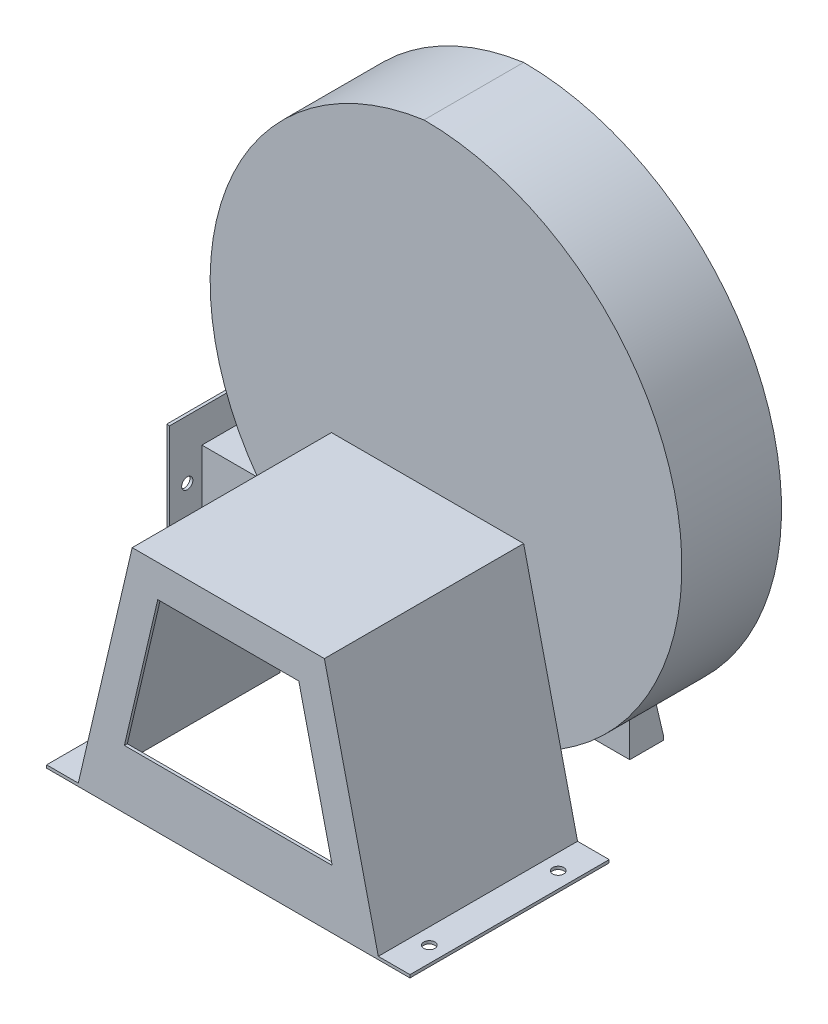
SolidWorks part; units mm, degrees
ref_plane "Alzado" through (0, 0, 0) normal (0, 0, 1) x (1, 0, 0)
ref_plane "Planta" through (0, 0, 0) normal (0, 1, 0) x (1, 0, 0)
ref_plane "Vista lateral" through (0, 0, 0) normal (1, 0, 0) x (0, 0, -1)
sketch "Croquis1" plane through (0, 0, 0) normal (0, 0, 1) x (1, 0, 0)
  line L0 (0, 0) -> (29, 0)
  line L1 (29, 0) -> (75, 197)
  line L2 (75, 197) -> (235, 197)
  line L3 (155, 197) -> (155, 0) construction
  line L4 (155, 0) -> (29, 0) construction
  line L5 (310, 0) -> (281, 0)
  line L6 (281, 0) -> (235, 197)
  line L7 (0, 2.5) -> (27.0165, 2.5)
  line L8 (27.0165, 2.5) -> (73.0165, 199.5)
  line L9 (73.0165, 199.5) -> (236.9835, 199.5)
  line L10 (282.9835, 2.5) -> (236.9835, 199.5)
  line L11 (310, 2.5) -> (282.9835, 2.5)
  line L12 (0, 2.5) -> (0, 0)
  line L13 (310, 2.5) -> (310, 0)
  dimension "D1" = 29
  dimension "D2" = 155
  dimension "D3" = 80
  dimension "D4" = 197
  dimension "D5" = 2.5
extrude "Saliente-Extruir1" add sketch "Croquis1" along normal blind 170
sketch "Croquis2" plane through (0, 0, 170) normal (0, 0, 1) x (1, 0, 0)
  line L0 (29, 0) -> (281, 0)
  line L1 (281, 0) -> (269.2863, 50.1652)
  line L2 (235, 197) -> (281, 0) construction
  line L3 (243.6524, 50) -> (66.3476, 50)
  line L4 (29, 0) -> (75, 197) construction
  line L5 (40.7137, 50.1652) -> (29, 0)
  line L6 (66.3476, 50) -> (94.8349, 172)
  line L7 (243.6524, 50) -> (215.1651, 172)
  line L8 (94.8349, 172) -> (215.1651, 172)
  line L9 (75, 197) -> (235, 197) construction
  line L10 (40.7137, 50.1652) -> (75, 197)
  line L11 (75, 197) -> (235, 197)
  line L12 (235, 197) -> (269.2863, 50.1652)
  dimension "D1" = 50
  dimension "D2" = 25
  dimension "D3" = 25
  dimension "D4" = 25
extrude "Saliente-Extruir2" add sketch "Croquis2" against normal blind 2.5
sketch "Croquis4" plane through (0, 2.5, 0) normal (0, 1, 0) x (1, 0, 0)
  line L0 (13.5083, 0) -> (13.5083, -170) construction
  line L1 (27.0165, 0) -> (0, 0) construction
  line L2 (27.0165, -170) -> (0, -170) construction
  line L3 (296.4917, 0) -> (296.4917, -170) construction
  line L4 (310, 0) -> (282.9835, 0) construction
  line L5 (310, -170) -> (282.9835, -170) construction
  line L6 (155, 0) -> (155, -170) construction
  line L7 (236.9835, 0) -> (73.0165, 0) construction
  line L8 (236.9835, -170) -> (73.0165, -170) construction
  circle A0 centre (13.5083, -30) radius 4.7625
  circle A1 centre (13.5083, -140) radius 4.7625
  circle A2 centre (296.4917, -140) radius 4.7625
  circle A3 centre (296.4917, -30) radius 4.7625
  dimension "D1" = 9.525
  dimension "D2" = 9.525
  dimension "D4" = 30
  dimension "D3" = 30
extrude "Cortar-Extruir1" cut sketch "Croquis4" against normal blind 2.5
sketch "Croquis5" plane through (0, 0, 0) normal (0, 0, -1) x (-1, 0, 0)
  line L0 (-281, 0) -> (-152, 0) construction
  line L1 (-152, 0) -> (-152, 470) construction
  line L2 (-29, 0) -> (-281, 0) construction
  line L3 (0, 30) -> (40, 30)
  line L4 (-152, 30) -> (0, 30)
  line L5 (0, 30) -> (0, 0) construction
  line L6 (40, 30) -> (40, 135)
  line L7 (40, 135) -> (-10, 135)
  arc A0 (-152, 470) -> (-152, 30) centre (-152, 250) ccw
  arc A1 (-152, 470) -> (-10, 135) centre (-181.8777, 259.7399) cw
  dimension "D1" = 470
  dimension "D2" = 30
  dimension "D3" = 40
  dimension "D4" = 105
  dimension "D5" = 50
  dimension "D6" = 152
extrude "Saliente-Extruir3" add sketch "Croquis5" along normal blind 2.5
sketch "Croquis6" plane through (0, 0, -2.5) normal (0, 0, -1) x (-1, 0, 0)
  line L0 (-10, 135) -> (40, 135)
  line L1 (40, 135) -> (40, 133)
  line L2 (40, 30) -> (-152, 30)
  line L3 (38, 32) -> (-152, 32)
  line L4 (-13.9685, 133) -> (38, 133)
  line L6 (38, 32) -> (40, 32)
  line L7 (38, 133) -> (40, 133)
  line L8 (40, 32) -> (40, 30)
  line L9 (40, 135) -> (40, 30) construction
  line L10 (38, 133) -> (38, 32) construction
  arc A0 (-152, 470) -> (-152, 30) centre (-152, 250) ccw
  arc A1 (-152, 470) -> (-152, 30) centre (-152, 250) ccw construction
  arc A2 (-152, 470) -> (-10, 135) centre (-181.8777, 259.7399) cw
  arc A3 (-152.1414, 468) -> (-152, 32) centre (-152, 250) ccw
  arc A4 (-152.1414, 468) -> (-13.9685, 133) centre (-181.8777, 259.7399) cw
  dimension "D1" = 2
extrude "Saliente-Extruir4" add sketch "Croquis6" along normal blind 80
sketch "Croquis7" plane through (0, 0, -82.5) normal (0, 0, -1) x (-1, 0, 0)
  line L0 (-10, 135) -> (40, 135)
  line L1 (40, 135) -> (40, 30)
  line L2 (40, 30) -> (-152, 30)
  arc A0 (-152, 470) -> (-152, 30) centre (-152, 250) ccw
  arc A1 (-152, 470) -> (-152, 30) centre (-152, 250) ccw construction
  arc A2 (-152, 470) -> (-10, 135) centre (-181.8777, 259.7399) cw
extrude "Saliente-Extruir5" add sketch "Croquis7" along normal blind 2.5
sketch "Croquis8" plane through (-40, 0, 0) normal (-1, 0, 0) x (0, 0, 1)
  line L0 (-112.5, 163) -> (-112.5, 2)
  line L1 (-82.5, 133) -> (-2.5, 133)
  line L2 (-82.5, 133) -> (-82.5, 32)
  line L3 (-82.5, 32) -> (-2.5, 32)
  line L4 (-2.5, 133) -> (-2.5, 32)
  line L5 (-112.5, 2) -> (27.5, 2)
  line L6 (27.5, 163) -> (27.5, 2)
  line L7 (-112.5, 163) -> (27.5, 163)
  dimension "D1" = 30
extrude "Saliente-Extruir6" add sketch "Croquis8" against normal blind 2.5
sketch "Croquis9" plane through (-40, 0, 0) normal (-1, 0, 0) x (0, 0, 1)
  line L0 (-42.5, 133) -> (-42.5, 163) construction
  line L1 (-82.5, 133) -> (-2.5, 133) construction
  line L2 (27.5, 163) -> (-112.5, 163) construction
  line L3 (-82.5, 82.5) -> (-112.5, 82.5) construction
  line L4 (-82.5, 32) -> (-82.5, 133) construction
  line L5 (-112.5, 163) -> (-112.5, 2) construction
  line L6 (-97.5, 82.5) -> (-97.5, 163) construction
  line L7 (-2.5, 82.5) -> (27.5, 82.5) construction
  line L8 (-2.5, 32) -> (-2.5, 133) construction
  line L9 (27.5, 2) -> (27.5, 163) construction
  line L10 (12.5, 82.5) -> (12.5, 163) construction
  line L11 (-42.5, 32) -> (-42.5, 2) construction
  circle A0 centre (-42.5, 148) radius 4.7625
  circle A1 centre (-97.5, 113) radius 4.7625
  circle A2 centre (12.5, 113) radius 4.7625
  circle A3 centre (12.5, 52) radius 4.7625
  circle A4 centre (-97.5, 52) radius 4.7625
  circle A5 centre (-42.5, 17) radius 4.7625
  dimension "D1" = 9.525
  dimension "D3" = 9.525
  dimension "D4" = 9.525
  dimension "D5" = 50
  dimension "D2" = 50
extrude "Cortar-Extruir2" cut sketch "Croquis9" against normal blind 2.5
sketch "Croquis10" plane through (0, 0, -85) normal (0, 0, -1) x (-1, 0, 0)
  line L0 (-155, 199.5) -> (-155, 279.5) construction
  line L1 (-236.9835, 199.5) -> (-73.0165, 199.5) construction
  circle A0 centre (-155, 279.5) radius 61
  dimension "D2" = 122
  dimension "D1" = 80
extrude "Cortar-Extruir3" cut sketch "Croquis10" against normal blind 2.5
sketch "Croquis11" plane through (0, 0, -85) normal (0, 0, -1) x (-1, 0, 0)
  circle A0 centre (-155, 279.5) radius 61
  circle A1 centre (-155, 279.5) radius 63.5
  dimension "D1" = 2.5
extrude "Saliente-Extruir7" add sketch "Croquis11" along normal blind 28.5
sketch "Croquis12" plane through (0, 0, -113.5) normal (0, 0, -1) x (-1, 0, 0)
  line L0 (-155, 340.5) -> (-155, 367.5) construction
  circle A0 centre (-155, 279.5) radius 61
  circle A1 centre (-155, 279.5) radius 88
  dimension "D1" = 27
extrude "Saliente-Extruir8" add sketch "Croquis12" against normal blind 2.5
sketch "Croquis13" plane through (0, 0, -85) normal (0, 0, -1) x (-1, 0, 0)
  line L0 (-155, 0) -> (-155, 115) construction
  line L1 (-29, 0) -> (-281, 0) construction
  line L3 (-242.5, 0) -> (-67.5, 0)
  line L4 (-242.5, 0) -> (-242.5, 115)
  line L5 (-242.5, 115) -> (-67.5, 115)
  line L6 (-67.5, 0) -> (-67.5, 115)
  line L7 (-242.5, 0) -> (-67.5, 115) construction
  line L8 (-242.5, 115) -> (-67.5, 0) construction
  point P4 (-155, 57.5)
  dimension "D1" = 115
  dimension "D2" = 175
extrude "Saliente-Extruir9" add sketch "Croquis13" along normal blind 2.5
sketch "Croquis14" plane through (0, 0, -87.5) normal (0, 0, -1) x (-1, 0, 0)
  line L0 (-67.5, 0) -> (-67.5, 115) construction
  line L1 (-242.5, 0) -> (-67.5, 0)
  line L2 (-242.5, 0) -> (-242.5, 2.5)
  line L3 (-242.5, 2.5) -> (-67.5, 2.5)
  line L4 (-67.5, 0) -> (-67.5, 2.5)
  dimension "D1" = 2.5
extrude "Saliente-Extruir10" add sketch "Croquis14" along normal blind 26.5
sketch "Croquis15" plane through (67.5, 0, 0) normal (-1, 0, 0) x (0, 0, 1)
  line L0 (-114, 2.5) -> (-87.5, 115)
  line L1 (-87.5, 115) -> (-85, 115)
  line L2 (-85, 115) -> (-85, 0)
  line L3 (-85, 0) -> (-114, 0)
  line L4 (-114, 0) -> (-114, 2.5)
extrude "Saliente-Extruir11" add sketch "Croquis15" against normal blind 2.5
sketch "Croquis16" plane through (242.5, 0, 0) normal (1, 0, 0) x (0, 0, -1)
  line L0 (114, 2.5) -> (87.5, 115)
  line L1 (87.5, 115) -> (85, 115)
  line L2 (85, 115) -> (85, 0)
  line L3 (85, 0) -> (114, 0)
  line L4 (114, 0) -> (114, 2.5)
extrude "Saliente-Extruir12" add sketch "Croquis16" against normal blind 2.5
sketch "Croquis17" plane through (0, 0, 0) normal (0, -1, 0) x (1, 0, 0)
  line L0 (240, -100.75) -> (70, -100.75) construction
  line L1 (240, -114) -> (240, -87.5) construction
  line L2 (70, -114) -> (70, -87.5) construction
  line L3 (242.5, -114) -> (242.5, -85) construction
  line L4 (67.5, -114) -> (67.5, -85) construction
  circle A0 centre (198.5, -100.75) radius 4.7625
  circle A1 centre (111.5, -100.75) radius 4.7625
  dimension "D1" = 9.525
  dimension "D2" = 9.525
  dimension "D3" = 44
  dimension "D4" = 44
extrude "Cortar-Extruir4" cut sketch "Croquis17" against normal blind 2.5
sketch "Croquis18" plane through (0, 0, -85) normal (0, 0, -1) x (-1, 0, 0)
  circle A0 centre (-155, 279.5) radius 154
  dimension "D1" = 308
extrude "Saliente-Extruir13" add sketch "Croquis18" along normal blind 2.5
sketch "Croquis19" plane through (0, 0, -87.5) normal (0, 0, -1) x (-1, 0, 0)
  line L0 (-1, 279.5) -> (-13, 279.5) construction
  circle A0 centre (-155, 279.5) radius 154 construction
  circle A1 centre (-13, 279.5) radius 3.9688
  dimension "D2" = 7.9375
  dimension "D1" = 12
extrude "Saliente-Extruir14" add sketch "Croquis19" along normal blind 16
pattern_circular "MatrizC1" count 6 every 60 about axis through (155, 279.5, 0) along (0, 0, 1) of "Saliente-Extruir14"
sketch "Croquis20" plane through (0, 0, -87.5) normal (0, 0, -1) x (-1, 0, 0)
  line L1 (-6.0718, 279.5) -> (-9.5359, 285.5)
  line L2 (-9.5359, 285.5) -> (-16.4641, 285.5)
  line L3 (-16.4641, 285.5) -> (-19.9282, 279.5)
  line L4 (-19.9282, 279.5) -> (-16.4641, 273.5)
  line L5 (-16.4641, 273.5) -> (-9.5359, 273.5)
  line L6 (-9.5359, 273.5) -> (-6.0718, 279.5)
  circle A0 centre (-13, 279.5) radius 3.9688
  circle A1 centre (-13, 279.5) radius 6 construction
  dimension "D1" = 12
extrude "Saliente-Extruir15" add sketch "Croquis20" along normal blind 7
pattern_circular "MatrizC3" count 6 every 60 about axis through (155, 279.5, 0) along (0, 0, 1) of "Saliente-Extruir15"
